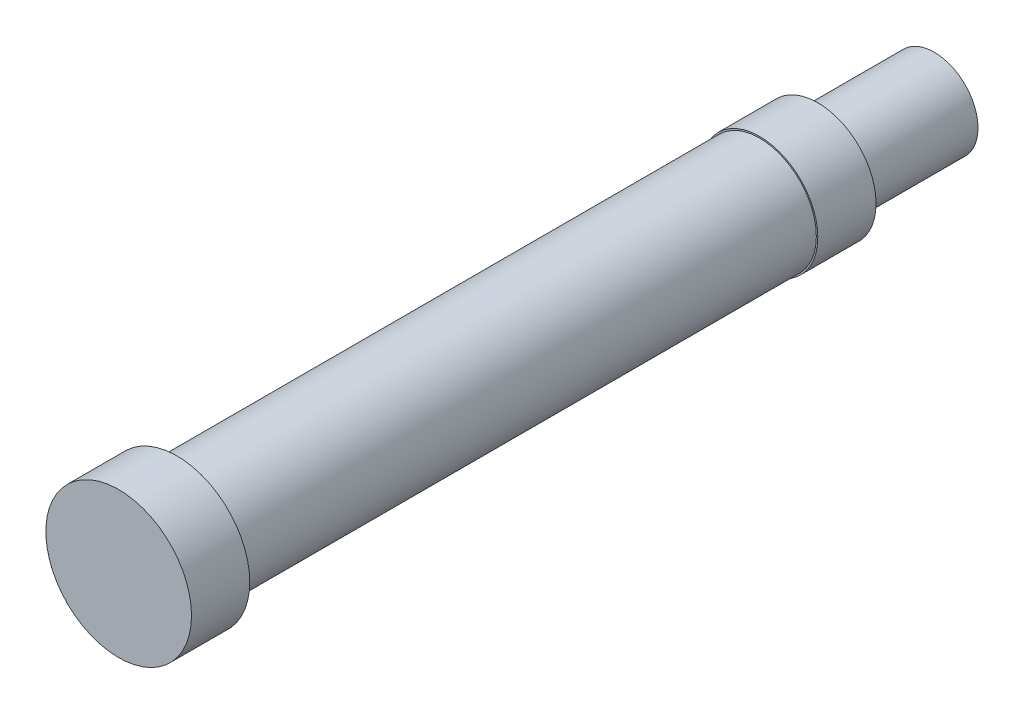
SolidWorks part; units mm, degrees
material "PLA"
ref_plane "Front Plane" through (0, 0, 0) normal (0, 0, 1) x (1, 0, 0)
ref_plane "Top Plane" through (0, 0, 0) normal (0, 1, 0) x (1, 0, 0)
ref_plane "Right Plane" through (0, 0, 0) normal (1, 0, 0) x (0, 0, -1)
sketch "Sketch1" plane through (0, 0, 0) normal (0, 0, 1) x (1, 0, 0)
  circle A0 centre (0, 0) radius 1.5
  dimension "D1" = 3
extrude "Boss-Extrude1" add sketch "Sketch1" along normal blind 4
sketch "Sketch2" plane through (0, 0, 4) normal (0, 0, 1) x (1, 0, 0)
  circle A0 centre (0, 0) radius 2
  dimension "D1" = 4
extrude "Boss-Extrude2" add sketch "Sketch2" along normal blind 2
sketch "Sketch3" plane through (0, 0, 6) normal (0, 0, 1) x (1, 0, 0)
  circle A0 centre (0, 0) radius 1.95
  dimension "D1" = 3.9
extrude "Boss-Extrude3" add sketch "Sketch3" along normal blind 20
sketch "Sketch4" plane through (0, 0, 26) normal (0, 0, 1) x (1, 0, 0)
  circle A0 centre (0, 0) radius 2.5
extrude "Boss-Extrude4" add sketch "Sketch4" along normal blind 2
